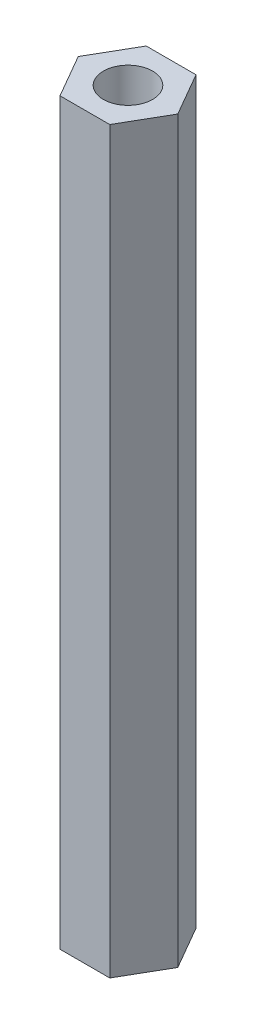
SolidWorks part; units mm, degrees
material "黄铜"
ref_plane "前视基准面" through (0, 0, 0) normal (0, 0, 1) x (1, 0, 0)
ref_plane "上视基准面" through (0, 0, 0) normal (0, 1, 0) x (1, 0, 0)
ref_plane "右视基准面" through (0, 0, 0) normal (1, 0, 0) x (0, 0, -1)
sketch "草图1" plane through (0, 0, 0) normal (0, 1, 0) x (1, 0, 0)
  line L1 (4.0415, 0) -> (2.0207, 3.5)
  line L2 (2.0207, 3.5) -> (-2.0207, 3.5)
  line L3 (-2.0207, 3.5) -> (-4.0415, 0)
  line L4 (-4.0415, 0) -> (-2.0207, -3.5)
  line L5 (-2.0207, -3.5) -> (2.0207, -3.5)
  line L6 (2.0207, -3.5) -> (4.0415, 0)
  circle A0 centre (0, 0) radius 2
  circle A1 centre (0, 0) radius 3.5 construction
  dimension "D1" = 4
  dimension "D2" = 7
extrude "凸台-拉伸1" add sketch "草图1" along normal blind 60
